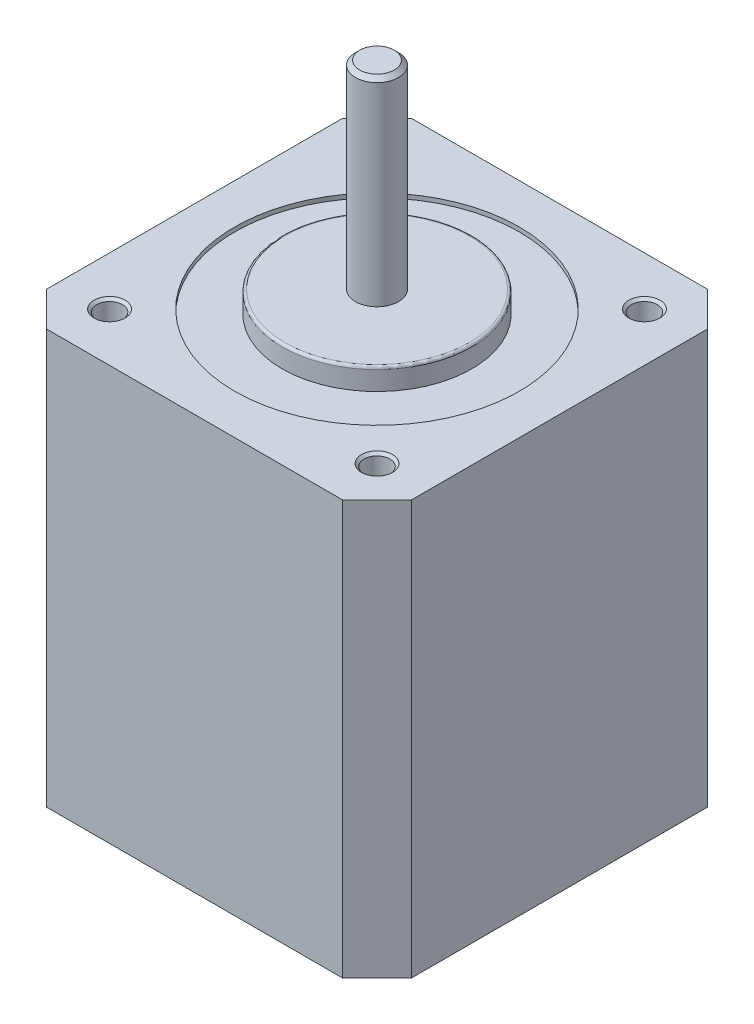
SolidWorks part; units mm, degrees
ref_plane "Front Plane" through (0, 0, 0) normal (0, 0, 1) x (1, 0, 0)
ref_plane "Top Plane" through (0, 0, 0) normal (0, 1, 0) x (1, 0, 0)
ref_plane "Right Plane" through (0, 0, 0) normal (1, 0, 0) x (0, 0, -1)
sketch "Sketch1" plane through (0, 0, 0) normal (0, 1, 0) x (1, 0, 0)
  line L1 (-21.15, -21.15) -> (21.15, -21.15)
  line L2 (-21.15, -21.15) -> (-21.15, 21.15)
  line L3 (-21.15, 21.15) -> (21.15, 21.15)
  line L4 (21.15, -21.15) -> (21.15, 21.15)
  line L5 (-21.15, -21.15) -> (21.15, 21.15) construction
  line L6 (-21.15, 21.15) -> (21.15, -21.15) construction
  point P0 (0, 0)
  dimension "D1" = 42.3
extrude "Boss-Extrude1" add sketch "Sketch1" along normal blind 48
sketch "Sketch2" plane through (0, 48, 0) normal (0, 1, 0) x (1, 0, 0)
  circle A0 centre (0, 0) radius 11
  dimension "D1" = 22
extrude "Boss-Extrude2" add sketch "Sketch2" along normal blind 2
sketch "Sketch3" plane through (0, 50, 0) normal (0, 1, 0) x (1, 0, 0)
  circle A0 centre (0, 0) radius 2.5
  dimension "D1" = 5
extrude "Boss-Extrude3" add sketch "Sketch3" along normal blind 23
fillet "Fillet2" radius 0.3 1 edges at (0, 50, 11)
chamfer "Chamfer1" distance 0.5 angle 45 1 edges at (0, 73, 2.5)
sketch "Sketch4" plane through (0, 48, 0) normal (0, 1, 0) x (1, 0, 0)
  line L0 (-15.5, -15.5) -> (15.5, -15.5) construction
  line L1 (15.5, -15.5) -> (15.5, 15.5) construction
  line L2 (15.5, 15.5) -> (-15.5, 15.5) construction
  line L3 (-15.5, 15.5) -> (-15.5, -15.5) construction
  line L4 (0, -15.5) -> (0, 15.5) construction
  line L5 (-15.5, 0) -> (15.5, 0) construction
  circle A0 centre (-15.5, -15.5) radius 1.5
  circle A1 centre (15.5, -15.5) radius 1.5
  circle A2 centre (15.5, 15.5) radius 1.5
  circle A3 centre (-15.5, 15.5) radius 1.5
  dimension "D2" = 3
  dimension "D1" = 31
extrude "Cut-Extrude1" cut sketch "Sketch4" against normal blind 4.5
chamfer "Chamfer2" distance 0.3 angle 45 4 edges at (15.5, 48, 17) (-15.5, 48, 17) (15.5, 48, -14) (-15.5, 48, -14)
sketch "Sketch5" plane through (0, 48, 0) normal (0, 1, 0) x (1, 0, 0)
  circle A0 centre (0, 0) radius 11
  circle A1 centre (0, 0) radius 16.5
  dimension "D1" = 22
  dimension "D2" = 33
extrude "Cut-Extrude2" cut sketch "Sketch5" against normal blind 0.5
sketch "Sketch6" plane through (0, 48, 0) normal (0, 1, 0) x (1, 0, 0)
  line L1 (-21.15, 21.15) -> (-21.15, -21.15) construction
  line L2 (-21.15, -17.15) -> (-17.15, -21.15)
  line L3 (-21.15, -21.15) -> (21.15, -21.15) construction
  line L5 (17.15, -21.15) -> (21.15, -17.15)
  line L6 (21.15, -21.15) -> (21.15, 21.15) construction
  line L8 (21.15, 17.15) -> (17.15, 21.15)
  line L9 (21.15, 21.15) -> (-21.15, 21.15) construction
  line L11 (-17.15, 21.15) -> (-21.15, 17.15)
  dimension "D1" = 45
  dimension "D2" = 4
extrude "Cut-Extrude-Thin1" cut sketch "Sketch6" against normal through all both and the other way through all thin
sketch "Sketch7" plane through (0, 0, 0) normal (0, -1, 0) x (1, 0, 0)
  circle A0 centre (0, 0) radius 3.5
  circle A1 centre (-15.5, 15.5) radius 3
  circle A2 centre (15.5, 15.5) radius 3
  circle A3 centre (15.5, -15.5) radius 3
  circle A4 centre (-15.5, -15.5) radius 3
  dimension "D1" = 6
  dimension "D2" = 7
extrude "Cut-Extrude3" cut sketch "Sketch7" against normal blind 5
sketch "Sketch8" plane through (-21.15, 0, 0) normal (-1, 0, 0) x (0, 0, 1)
  line L0 (-17.15, 0) -> (17.15, 0) construction
  line L1 (-4, 7.5) -> (4, 7.5)
  line L2 (-4, 7.5) -> (-4, 2.5)
  line L3 (-4, 2.5) -> (4, 2.5)
  line L4 (4, 7.5) -> (4, 2.5)
  line L5 (-4, 7.5) -> (4, 2.5) construction
  line L6 (-4, 2.5) -> (4, 7.5) construction
  point P0 (0, 5)
  dimension "D1" = 5
  dimension "D2" = 8
  dimension "D3" = 5
extrude "Boss-Extrude4" add sketch "Sketch8" along normal blind 2
fillet "Fillet3" radius 1 4 edges at (-23.15, 5, -4) (-23.15, 2.5, 0) (-23.15, 7.5, 0) (-23.15, 5, 4)
